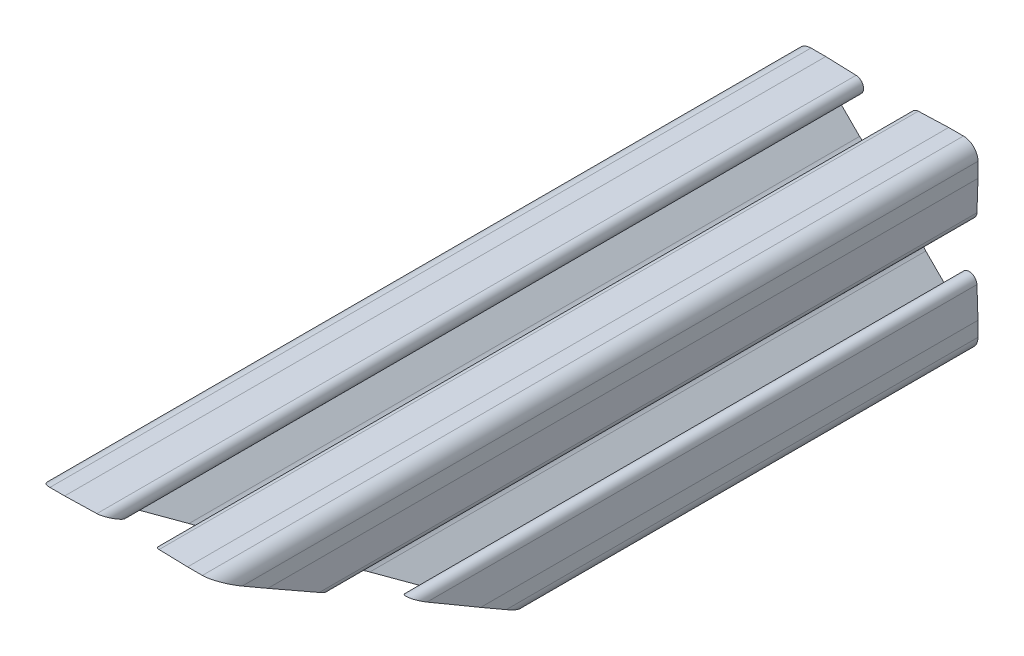
SolidWorks part; units mm, degrees
ref_plane "Front Plane" through (0, 0, 0) normal (0, 0, 1) x (1, 0, 0)
ref_plane "Top Plane" through (0, 0, 0) normal (0, 1, 0) x (1, 0, 0)
ref_plane "Right Plane" through (0, 0, 0) normal (1, 0, 0) x (0, 0, -1)
sketch "Model" plane through (0, 0, 0) normal (0, 0, 1) x (1, 0, 0)
  line L38 (50.6495, 75.4336) -> (50.2699, 75.4336)
  line L39 (50.2699, 75.4336) -> (50.2699, 75.8133)
  line L40 (50.66, 72.9999) -> (53.7746, 72.9999)
  line L41 (56.0196, 72.0699) -> (59.2642, 68.8254)
  line L42 (58.5103, 67.0916) -> (56.5725, 67.1592)
  line L43 (56.498, 65.0269) -> (60.6773, 64.881)
  line L44 (60.6773, 64.881) -> (62.7107, 64.881)
  line L45 (64.7173, 66.8876) -> (64.7173, 68.921)
  line L46 (64.7173, 68.921) -> (64.5713, 73.1002)
  line L47 (62.439, 73.0257) -> (62.5067, 71.0879)
  line L48 (60.7729, 70.334) -> (57.5283, 73.5786)
  line L49 (56.5984, 75.8237) -> (56.5984, 78.9383)
  line L50 (57.5283, 81.1833) -> (60.7729, 84.4279)
  line L51 (62.5067, 83.674) -> (62.439, 81.7362)
  line L52 (64.5713, 81.6617) -> (64.7173, 85.841)
  line L53 (64.7173, 85.841) -> (64.7173, 87.8744)
  line L54 (62.7107, 89.881) -> (60.6773, 89.881)
  line L55 (60.6773, 89.881) -> (56.498, 89.735)
  line L56 (56.5725, 87.6027) -> (58.5103, 87.6704)
  line L57 (59.2642, 85.9366) -> (56.0196, 82.692)
  line L58 (53.7746, 81.7621) -> (50.66, 81.7621)
  line L59 (48.4149, 82.692) -> (45.1703, 85.9366)
  line L60 (45.9242, 87.6704) -> (47.862, 87.6027)
  line L61 (47.9365, 89.735) -> (43.7573, 89.881)
  line L62 (43.7573, 89.881) -> (41.7239, 89.881)
  line L63 (39.7173, 87.8744) -> (39.7173, 85.841)
  line L64 (39.7173, 85.841) -> (39.8632, 81.6617)
  line L65 (41.9955, 81.7362) -> (41.9278, 83.674)
  line L66 (43.6616, 84.4279) -> (46.9062, 81.1833)
  line L67 (47.8361, 78.9383) -> (47.8361, 75.8237)
  line L68 (46.9062, 73.5786) -> (43.6616, 70.334)
  line L69 (41.9278, 71.0879) -> (41.9955, 73.0257)
  line L70 (39.8632, 73.1002) -> (39.7173, 68.921)
  line L71 (39.7173, 68.921) -> (39.7173, 66.8876)
  line L72 (41.7239, 64.881) -> (43.7573, 64.881)
  line L73 (43.7573, 64.881) -> (47.9365, 65.0269)
  line L74 (47.862, 67.1592) -> (45.9242, 67.0916)
  line L75 (45.1703, 68.8254) -> (48.4149, 72.0699)
  arc A29 (50.6495, 75.4336) -> (50.2699, 75.8133) centre (52.2173, 77.381) ccw
  arc A30 (56.0196, 72.0699) -> (53.7746, 72.9999) centre (53.7746, 69.8249) ccw
  arc A31 (58.5103, 67.0916) -> (59.2642, 68.8254) centre (58.5458, 68.1069) ccw
  arc A32 (56.5725, 67.1592) -> (56.498, 65.0269) centre (56.5353, 66.0931) ccw
  arc A33 (62.7107, 64.881) -> (64.7173, 66.8876) centre (62.7107, 66.8876) ccw
  arc A34 (64.5713, 73.1002) -> (62.439, 73.0257) centre (63.5052, 73.063) ccw
  arc A35 (60.7729, 70.334) -> (62.5067, 71.0879) centre (61.4913, 71.0525) ccw
  arc A36 (56.5984, 75.8237) -> (57.5283, 73.5786) centre (59.7734, 75.8237) ccw
  arc A37 (57.5283, 81.1833) -> (56.5984, 78.9383) centre (59.7734, 78.9383) ccw
  arc A38 (62.5067, 83.674) -> (60.7729, 84.4279) centre (61.4913, 83.7095) ccw
  arc A39 (62.439, 81.7362) -> (64.5713, 81.6617) centre (63.5052, 81.699) ccw
  arc A40 (64.7173, 87.8744) -> (62.7107, 89.881) centre (62.7107, 87.8744) ccw
  arc A41 (56.498, 89.735) -> (56.5725, 87.6027) centre (56.5353, 88.6689) ccw
  arc A42 (59.2642, 85.9366) -> (58.5103, 87.6704) centre (58.5458, 86.655) ccw
  arc A43 (53.7746, 81.7621) -> (56.0196, 82.692) centre (53.7746, 84.9371) ccw
  arc A44 (48.4149, 82.692) -> (50.66, 81.7621) centre (50.66, 84.9371) ccw
  arc A45 (45.9242, 87.6704) -> (45.1703, 85.9366) centre (45.8887, 86.655) ccw
  arc A46 (47.862, 87.6027) -> (47.9365, 89.735) centre (47.8993, 88.6689) ccw
  arc A47 (41.7239, 89.881) -> (39.7173, 87.8744) centre (41.7239, 87.8744) ccw
  arc A48 (39.8632, 81.6617) -> (41.9955, 81.7362) centre (40.9293, 81.699) ccw
  arc A49 (43.6616, 84.4279) -> (41.9278, 83.674) centre (42.9432, 83.7095) ccw
  arc A50 (47.8361, 78.9383) -> (46.9062, 81.1833) centre (44.6611, 78.9383) ccw
  arc A51 (46.9062, 73.5786) -> (47.8361, 75.8237) centre (44.6611, 75.8237) ccw
  arc A52 (41.9278, 71.0879) -> (43.6616, 70.334) centre (42.9432, 71.0525) ccw
  arc A53 (41.9955, 73.0257) -> (39.8632, 73.1002) centre (40.9293, 73.063) ccw
  arc A54 (39.7173, 66.8876) -> (41.7239, 64.881) centre (41.7239, 66.8876) ccw
  arc A55 (47.9365, 65.0269) -> (47.862, 67.1592) centre (47.8993, 66.0931) ccw
  arc A56 (45.1703, 68.8254) -> (45.9242, 67.0916) centre (45.8887, 68.1069) ccw
  arc A57 (50.66, 72.9999) -> (48.4149, 72.0699) centre (50.66, 69.8249) ccw
extrude "Boss-Extrude1" add sketch "Model" along normal blind 104.775
sketch "Sketch1" plane through (64.7173, 0, 0) normal (1, 0, 0) x (0, 0, -1)
  line L0 (-104.775, 89.881) -> (-104.775, 64.881)
  line L1 (-104.775, 64.881) -> (-61.4737, 64.881)
  line L2 (-104.775, 64.881) -> (0, 64.881) construction
  line L3 (-61.4737, 64.881) -> (-104.775, 89.881)
  dimension "D1" = 60
extrude "Cut-Extrude1" cut sketch "Sketch1" against normal through all
sketch "Sketch2" plane through (0, 22.0418, -12.7259) normal (0, -0.866, 0.5) x (1, 0, 0)
  line L0 (52.2173, 101.9161) -> (52.2173, 119.4405) construction
  line L3 (53.7746, 101.9161) -> (50.66, 101.9161) construction
  line L4 (50.66, 119.4405) -> (53.7746, 119.4405) construction
  line L5 (47.8361, 110.6783) -> (56.5984, 110.6783) construction
  line L6 (47.8361, 107.5637) -> (47.8361, 113.7929) construction
  line L7 (56.5984, 113.7929) -> (56.5984, 107.5637) construction
  circle A0 centre (52.2173, 110.6783) radius 2.54
  dimension "D1" = 5.08
extrude "Cut-Extrude2" cut sketch "Sketch2" against normal through all
